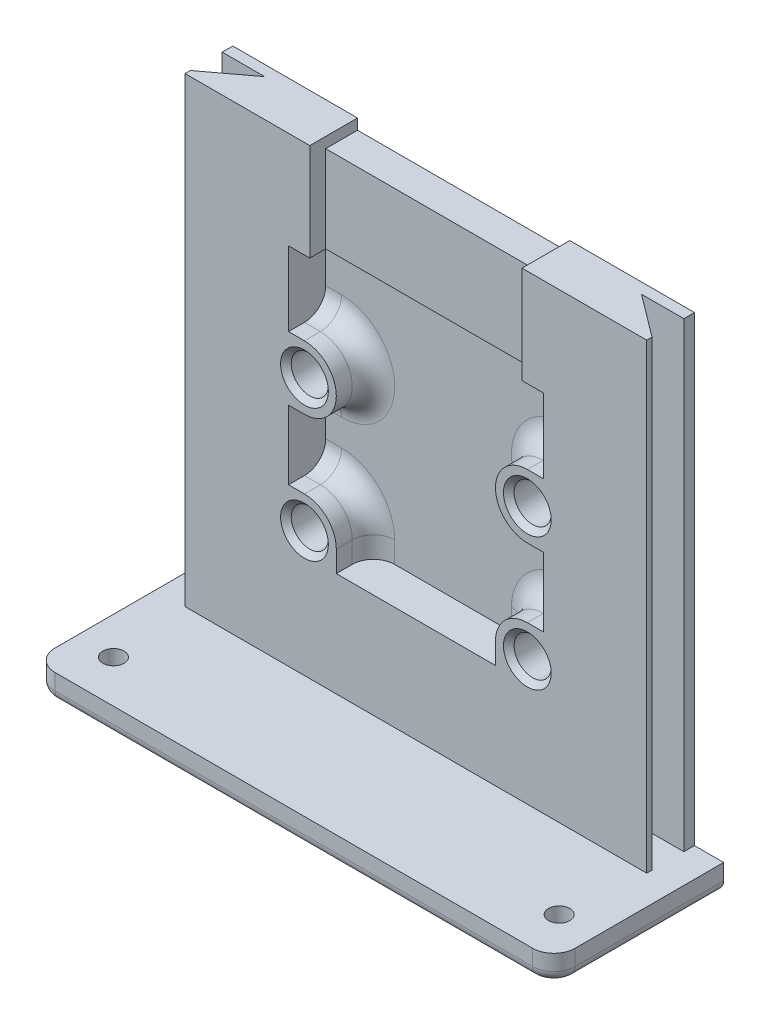
SolidWorks part; units mm, degrees
ref_plane "Plan de face" through (0, 0, 0) normal (0, 0, 1) x (1, 0, 0)
ref_plane "Plan de dessus" through (0, 0, 0) normal (0, 1, 0) x (1, 0, 0)
ref_plane "Plan de droite" through (0, 0, 0) normal (1, 0, 0) x (0, 0, -1)
sketch "Esquisse1" plane through (0, 0, 0) normal (0, 0, 1) x (1, 0, 0)
  line L1 (0, 0) -> (43.5, 0)
  line L2 (0, 0) -> (0, 43.5)
  line L3 (0, 43.5) -> (43.5, 43.5)
  line L4 (43.5, 0) -> (43.5, 43.5)
  dimension "D1" = 43.5
  dimension "D2" = 43.5
extrude "Boss.-Extru.1" add sketch "Esquisse1" along normal blind 3.5
sketch "Esquisse3" plane through (0, 0, 3.5) normal (0, 0, 1) x (1, 0, 0)
  line L0 (0, 43.5) -> (0, 0) construction
  line L1 (9.75, 34.32) -> (33.75, 34.32)
  line L2 (9.75, 34.32) -> (9.75, 9.82)
  line L3 (9.75, 9.82) -> (33.75, 9.82)
  line L4 (33.75, 34.32) -> (33.75, 9.82)
  line L5 (43.5, 0) -> (43.5, 43.5) construction
  line L6 (43.5, 43.5) -> (0, 43.5) construction
  dimension "D1" = 24
  dimension "D2" = 24.5
  dimension "D3" = 9.75
  dimension "D4" = 9.75
  dimension "D5" = 9.18
extrude "Enlèv. mat.-Extru.1" cut sketch "Esquisse3" against normal blind 3.5
sketch "Esquisse4" plane through (0, 0, 0) normal (0, -1, 0) x (1, 0, 0)
  line L13 (0, 0) -> (0, 3)
  line L14 (0, 3.5) -> (0, 0) construction
  line L15 (0, 3) -> (4, 0)
  line L16 (0, 0) -> (43.5, 0) construction
  line L17 (4, 0) -> (0, 0)
  line L18 (43.5, 3) -> (39.5, 0)
  line L19 (43.5, 3.5) -> (43.5, 0) construction
  line L20 (39.5, 0) -> (43.5, 0)
  line L21 (43.5, 0) -> (43.5, 3)
  dimension "D1" = 4
  dimension "D2" = 3
  dimension "D3" = 4
  dimension "D4" = 3
extrude "Enlèv. mat.-Extru.3" cut sketch "Esquisse4" against normal blind 43.5
sketch "Esquisse5" plane through (0, 0, 3.5) normal (0, 0, 1) x (1, 0, 0)
  line L0 (43.5, 43.5) -> (0, 43.5) construction
  line L1 (11.75, 43.5) -> (31.75, 43.5)
  line L2 (11.75, 43.5) -> (11.75, 34.32)
  line L3 (11.75, 34.32) -> (31.75, 34.32)
  line L4 (31.75, 43.5) -> (31.75, 34.32)
  line L5 (33.75, 34.32) -> (9.75, 34.32) construction
  line L6 (0, 43.5) -> (0, 0) construction
  line L7 (43.5, 0) -> (43.5, 43.5) construction
  dimension "D1" = 11.75
  dimension "D2" = 20
  dimension "D3" = 11.75
extrude "Enlèv. mat.-Extru.4" cut sketch "Esquisse5" against normal blind 1.5
sketch "Esquisse6" plane through (0, 0, 3.5) normal (0, 0, 1) x (1, 0, 0)
  line L0 (9.75, 9.82) -> (33.75, 9.82) construction
  line L1 (33.75, 9.82) -> (33.75, 34.32) construction
  line L2 (11.25, 27.32) -> (9.75, 27.32)
  line L3 (9.75, 34.32) -> (9.75, 9.82) construction
  line L4 (9.75, 27.32) -> (9.75, 21.32)
  line L5 (9.75, 21.32) -> (11.25, 21.32)
  line L6 (11.25, 14.82) -> (9.75, 14.82)
  line L7 (9.75, 14.82) -> (9.75, 9.82)
  line L8 (9.75, 9.82) -> (14.25, 9.82)
  line L9 (14.25, 9.82) -> (14.25, 11.82)
  line L10 (29.25, 11.82) -> (29.25, 9.82)
  line L11 (29.25, 9.82) -> (33.75, 9.82)
  line L12 (33.75, 9.82) -> (33.75, 14.82)
  line L13 (33.75, 14.82) -> (32.25, 14.82)
  line L14 (32.25, 27.32) -> (33.75, 27.32)
  line L15 (33.75, 27.32) -> (33.75, 21.32)
  line L16 (33.75, 21.32) -> (32.25, 21.32)
  arc A0 (11.25, 21.32) -> (11.25, 27.32) centre (11.25, 24.32) ccw
  arc A1 (32.25, 27.32) -> (32.25, 21.32) centre (32.25, 24.32) ccw
  arc A2 (32.25, 14.82) -> (29.25, 11.82) centre (32.25, 11.82) ccw
  arc A3 (14.25, 11.82) -> (11.25, 14.82) centre (11.25, 11.82) ccw
  dimension "D7" = 6
  dimension "D8" = 6
  dimension "D9" = 6
  dimension "D10" = 6
  dimension "D1" = 12.5
  dimension "D2" = 0
  dimension "D3" = 21
  dimension "D4" = 0
  dimension "D5" = 2
  dimension "D6" = 1.5
  dimension "D11" = 21
  dimension "D12" = 12.5
extrude "Boss.-Extru.2" add sketch "Esquisse6" against normal blind 3.5
sketch "Esquisse8" plane through (0, 0, 3.5) normal (0, 0, 1) x (1, 0, 0)
  circle A0 centre (11.25, 24.32) radius 1.75
  circle A1 centre (32.25, 24.32) radius 1.75
  circle A2 centre (32.25, 11.82) radius 1.75
  circle A3 centre (11.25, 11.82) radius 1.75
  dimension "D1" = 3.5
  dimension "D2" = 3.5
  dimension "D3" = 3.5
  dimension "D4" = 3.5
extrude "Enlèv. mat.-Extru.5" cut sketch "Esquisse8" against normal blind 3.5
sketch "Esquisse9" plane through (0, 0, 0) normal (0, 0, -1) x (-1, 0, 0)
  line L1 (-43.5, 43.5) -> (0, 43.5)
  line L2 (-43.5, 43.5) -> (-43.5, 0)
  line L3 (-43.5, 0) -> (0, 0)
  line L4 (0, 43.5) -> (0, 0)
extrude "Boss.-Extru.3" add sketch "Esquisse9" along normal blind 1
fillet "Congé2" radius 2 12 edges at (33, 21.32, 0) (33, 27.32, 0) (29.25, 24.32, 0) (29.25, 10.82, 0) (30.1287, 13.9413, 0) (33, 14.82, 0) (10.5, 21.32, 0) (10.5, 27.32, 0) (10.5, 14.82, 0) (14.25, 10.82, 0) (13.3713, 13.9413, 0) (14.25, 24.32, 0)
chamfer "Chanfrein1" distance 0.5 angle 45 4 edges at (13, 11.82, 3.5) (34, 24.32, 3.5) (13, 24.32, 3.5) (34, 11.82, 3.5)
sketch "Esquisse10" plane through (0, 0, 2) normal (0, 0, 1) x (1, 0, 0)
  line L0 (31.75, 34.32) -> (31.75, 43.5) construction
  line L1 (11.75, 43.5) -> (31.75, 43.5)
  line L2 (11.75, 43.5) -> (11.75, 42.5)
  line L3 (11.75, 42.5) -> (31.75, 42.5)
  line L4 (31.75, 43.5) -> (31.75, 42.5)
  dimension "D1" = 1
extrude "Enlèv. mat.-Extru.6" cut sketch "Esquisse10" against normal blind 3
sketch "Esquisse11" plane through (0, 0, 0) normal (0, -1, 0) x (1, 0, 0)
  line L0 (0, -1) -> (0, 0) construction
  line L1 (-2.75, -1) -> (46.25, -1)
  line L2 (-2.75, -1) -> (-2.75, 15)
  line L3 (-2.75, 15) -> (46.25, 15)
  line L4 (46.25, -1) -> (46.25, 15)
  line L6 (43.5, -1) -> (43.5, 0) construction
  dimension "D1" = 49
  dimension "D2" = 16
  dimension "D3" = 2.75
  dimension "D4" = 2.75
extrude "Boss.-Extru.4" add sketch "Esquisse11" along normal blind 2.5
sketch "Esquisse12" plane through (0, -2.5, 0) normal (0, -1, 0) x (1, 0, 0)
  line L1 (-2.75, 15) -> (-2.75, -1) construction
  line L2 (46.25, 15) -> (-2.75, 15) construction
  circle A0 centre (0.75, 11) radius 1
  circle A1 centre (42.75, 11) radius 1
  dimension "D4" = 2
  dimension "D5" = 2
  dimension "D1" = 3.5
  dimension "D2" = 42
  dimension "D3" = 4
extrude "Enlèv. mat.-Extru.7" cut sketch "Esquisse12" against normal blind 2.5
fillet "Congé3" radius 2 2 edges at (-2.75, -1.25, 15) (46.25, -1.25, 15)
fillet "Congé4" radius 1 5 edges at (46.25, -2.5, 6) (45.6642, -2.5, 14.4142) (21.75, -2.5, 15) (-2.1642, -2.5, 14.4142) (-2.75, -2.5, 6)
chamfer "Chanfrein2" distance 0.5 angle 45 2 edges at (42.75, -2.5, 10) (0.75, -2.5, 10)
